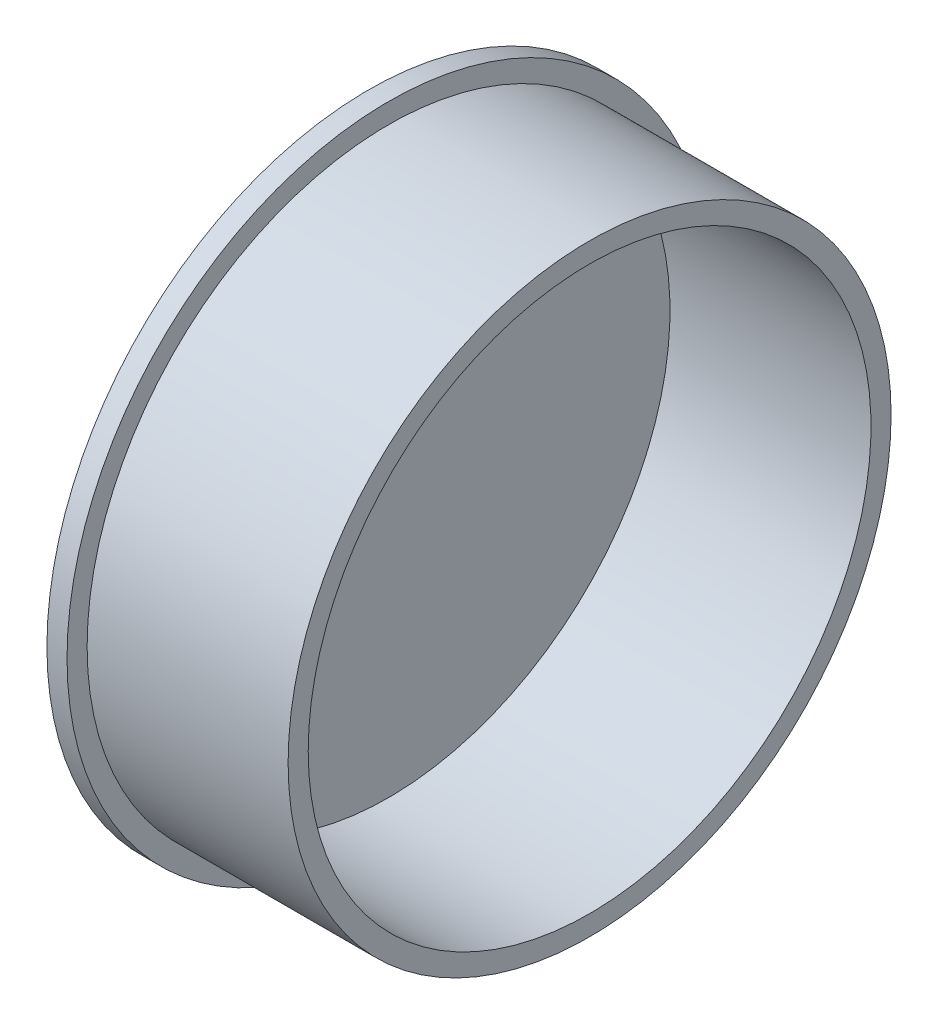
SolidWorks part; units mm, degrees
ref_plane "Ebene vorne" through (0, 0, 0) normal (0, 0, 1) x (1, 0, 0)
ref_plane "Ebene oben" through (0, 0, 0) normal (0, 1, 0) x (1, 0, 0)
ref_plane "Ebene rechts" through (0, 0, 0) normal (1, 0, 0) x (0, 0, -1)
sketch "Skizze1" plane through (0, 0, 0) normal (0, 0, 1) x (1, 0, 0)
  line L0 (0, 0) -> (100, 0) construction
  line L2 (0, 0) -> (-5, 0)
  line L3 (0, 0) -> (0, 80)
  line L4 (0, 80) -> (-5, 80)
  line L5 (-5, 0) -> (-5, 80)
  line L6 (0, 75) -> (50, 75)
  line L7 (0, 75) -> (0, 70)
  line L8 (0, 70) -> (50, 70)
  line L9 (50, 75) -> (50, 70)
  dimension "D1" = 100
  dimension "D2" = 80
  dimension "D3" = 5
  dimension "D4" = 5
  dimension "D5" = 50
  dimension "D6" = 5
revolve "Rotation1" add sketch "Skizze1" angle 360 about L0
